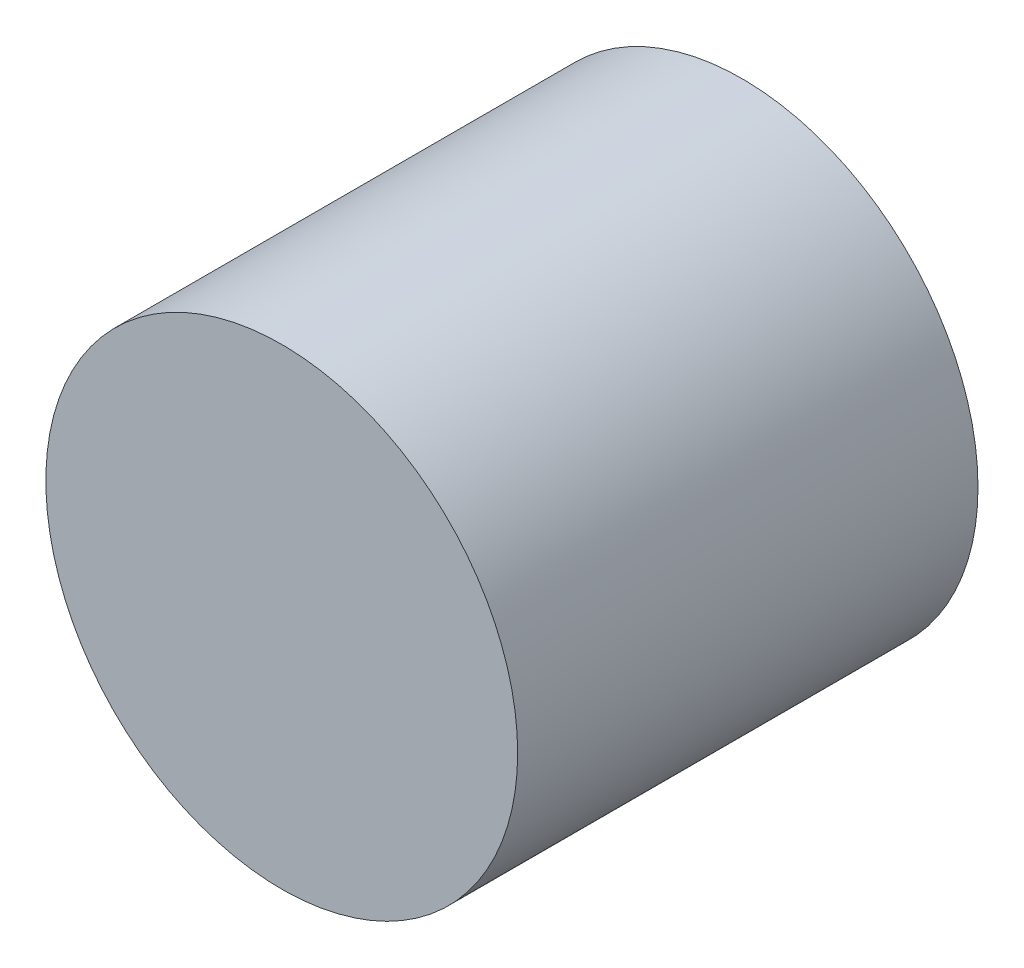
SolidWorks part; units mm, degrees
ref_plane "前视基准面" through (0, 0, 0) normal (0, 0, 1) x (1, 0, 0)
ref_plane "上视基准面" through (0, 0, 0) normal (0, 1, 0) x (1, 0, 0)
ref_plane "右视基准面" through (0, 0, 0) normal (1, 0, 0) x (0, 0, -1)
other "Configuration Table"
sketch "草图1" plane through (0, 0, 0) normal (0, 0, 1) x (1, 0, 0)
  line L0 (0, -8) -> (85, -8)
  line L1 (85, -8) -> (85, 8)
  line L2 (85, 8) -> (0, 8)
  line L3 (0, 8) -> (0, -8)
extrude "凸台-拉伸1" add sketch "草图1" along normal blind 8
sketch "草图2" plane through (0, 0, 0) normal (0, 0, 1) x (1, 0, 0)
  circle A0 centre (0, 0) radius 11
extrude "凸台-拉伸2" add sketch "草图2" along normal blind 8
sketch "草图3" plane through (0, 0, 0) normal (0, 0, 1) x (1, 0, 0)
  line L0 (85, -8) -> (85, 8) construction
  circle A0 centre (85, 0) radius 11
extrude "凸台-拉伸3" add sketch "草图3" along normal blind 8
sketch "草图4" plane through (0, 0, 8) normal (0, 0, 1) x (1, 0, 0)
  circle A0 centre (0, 0) radius 4.1
extrude "切除-拉伸1" cut sketch "草图4" against normal through all flip side to cut
sketch "草图5" plane through (0, 0, 0) normal (0, 0, 1) x (1, 0, 0)
  circle A0 centre (85, 0) radius 4.1
